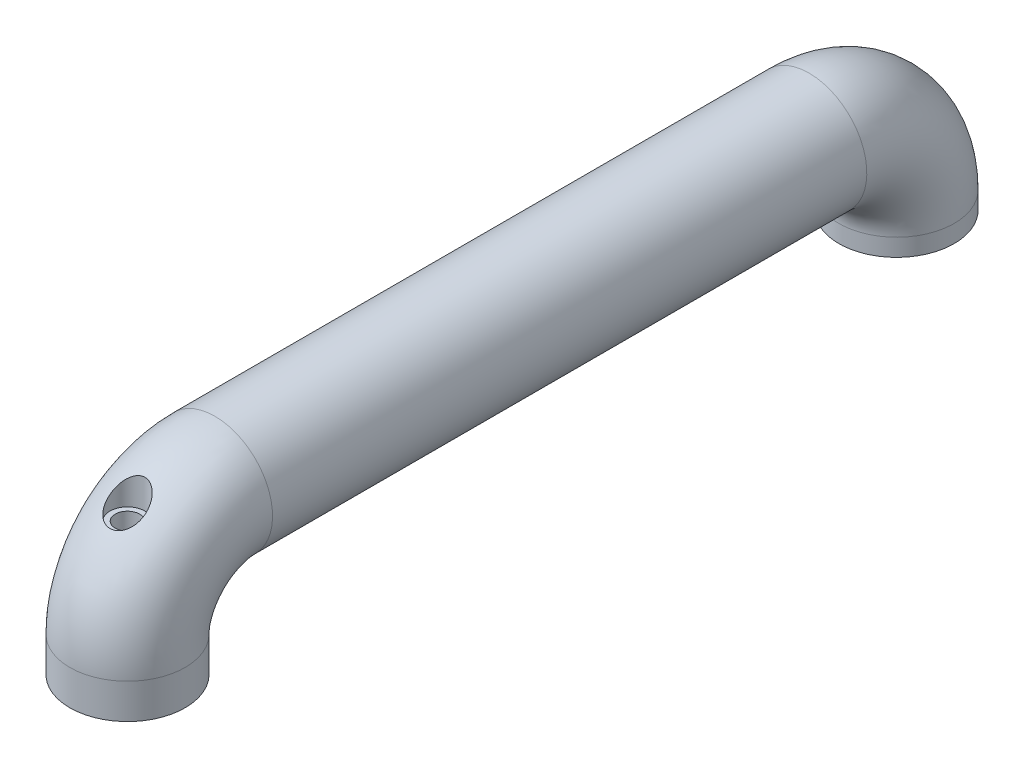
SolidWorks part; units mm, degrees
material "1060 Alloy"
ref_plane "Front Plane" through (0, 0, 0) normal (0, 0, 1) x (1, 0, 0)
ref_plane "Top Plane" through (0, 0, 0) normal (0, 1, 0) x (1, 0, 0)
ref_plane "Right Plane" through (0, 0, 0) normal (1, 0, 0) x (0, 0, -1)
sketch "Sketch1" plane through (0, 0, 0) normal (1, 0, 0) x (0, 0, -1)
  line L0 (81.4725, -41.8462) -> (81.4725, -36.8462)
  line L1 (56.4725, -11.8462) -> (-113.5275, -11.8462)
  line L2 (-138.5275, -36.8462) -> (-138.5275, -46.8462)
  arc A0 (-113.5275, -11.8462) -> (-138.5275, -36.8462) centre (-113.5275, -36.8462) ccw
  arc A1 (81.4725, -36.8462) -> (56.4725, -11.8462) centre (56.4725, -36.8462) ccw
  point P6 (-138.5275, -11.8462)
  point P9 (81.4725, -11.8462)
  dimension "D4" = 25
  dimension "D1" = 220
  dimension "D2" = 35
  dimension "D3" = 30
sweep "Sweep1" add path "Sketch1" circular profile diameter 33 parameters "D3"=33
sketch "Sketch10" plane through (0, -46.8462, 0) normal (0, -1, 0) x (1, 0, 0)
  line L1 (-8.5, 130.0275) -> (8.5, 130.0275)
  line L2 (-8.5, 130.0275) -> (-8.5, 147.0275)
  line L3 (-8.5, 147.0275) -> (8.5, 147.0275)
  line L4 (8.5, 130.0275) -> (8.5, 147.0275)
  line L5 (-8.5, 130.0275) -> (8.5, 147.0275) construction
  line L6 (-8.5, 147.0275) -> (8.5, 130.0275) construction
  point P0 (0, 138.5275)
  dimension "D1" = 17
  dimension "D2" = 17
extrude "Cut-Extrude1" cut sketch "Sketch10" against normal blind 25
sketch "Sketch11" plane through (0, -21.8462, 0) normal (0, -1, 0) x (1, 0, 0)
  circle A0 centre (0, 138.5275) radius 3.5
  dimension "D1" = 7
extrude "Cut-Extrude2" cut sketch "Sketch11" against normal blind 13
sketch "Sketch12" plane through (0, -8.8462, 0) normal (0, -1, 0) x (1, 0, 0)
  circle A0 centre (0, 138.5275) radius 5
  dimension "D1" = 10
extrude "Cut-Extrude3" cut sketch "Sketch12" against normal blind 13
